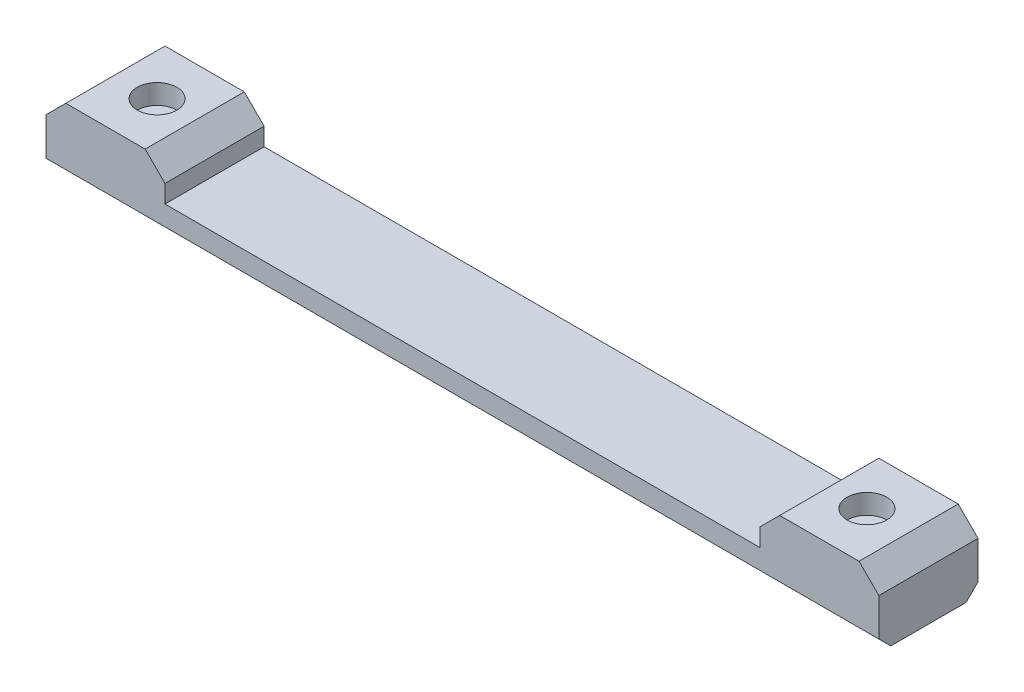
SolidWorks part; units mm, degrees
ref_plane "前视基准面" through (0, 0, 0) normal (0, 0, 1) x (1, 0, 0)
ref_plane "上视基准面" through (0, 0, 0) normal (0, 1, 0) x (1, 0, 0)
ref_plane "右视基准面" through (0, 0, 0) normal (1, 0, 0) x (0, 0, -1)
sketch "草图1" plane through (0, 0, 0) normal (0, 1, 0) x (1, 0, 0)
  line L0 (-131.8948, 0) -> (149.7141, 0) construction
  line L1 (-105, 12.5) -> (105, 12.5)
  line L2 (-105, 12.5) -> (-105, -12.5)
  line L3 (-105, -12.5) -> (105, -12.5)
  line L4 (105, 12.5) -> (105, -12.5)
  line L5 (0, 33.2521) -> (0, -27.5245) construction
  dimension "D1" = 25
  dimension "D2" = 210
extrude "凸台-拉伸1" add sketch "草图1" along normal blind 9.5 and the other way blind 8
sketch "草图2" plane through (0, 9.5, 0) normal (0, 1, 0) x (1, 0, 0)
  line L0 (105, 12.5) -> (-105, 12.5) construction
  line L1 (-75, 12.5) -> (75, 12.5)
  line L2 (-75, 12.5) -> (-75, -12.5)
  line L3 (-75, -12.5) -> (75, -12.5)
  line L4 (75, 12.5) -> (75, -12.5)
  line L5 (-105, -12.5) -> (105, -12.5) construction
  line L6 (0, 42.1834) -> (0, -40.2768) construction
  dimension "D1" = 150
extrude "切除-拉伸1" cut sketch "草图2" against normal offset from surface (9.5 mm away) 8 up to face at (0, -8, 0)
sketch "草图3" plane through (0, 9.5, 0) normal (0, 1, 0) x (1, 0, 0)
  line L0 (-152.3247, 0) -> (153.2738, 0) construction
  line L1 (0, 34.5692) -> (0, -30.2835) construction
  circle A0 centre (-89.5, 0) radius 5
  circle A1 centre (89.5, 0) radius 5
  dimension "D1" = 10
  dimension "D2" = 179
extrude "切除-拉伸2" cut sketch "草图3" against normal blind 5
chamfer "倒角1" distance 5 angle 45 4 edges at (105, 9.5, 0) (75, 9.5, 0) (-75, 9.5, 0) (-105, 9.5, 0)
chamfer "倒角2" distance 3 angle 45 2 edges at (0, -8, -12.5) (0, -8, 12.5)
